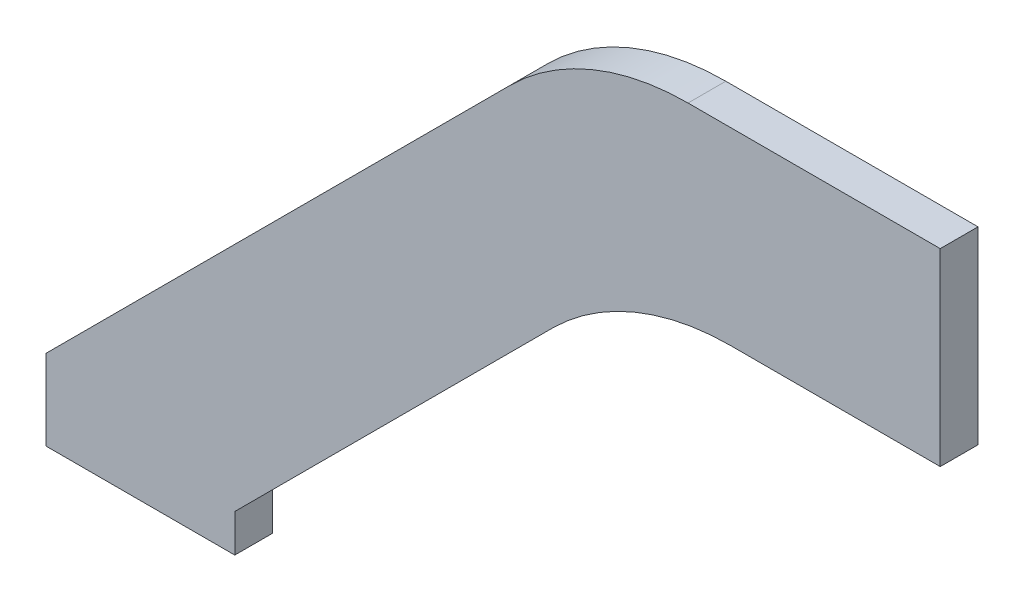
SolidWorks part; units mm, degrees
material "PBT General Purpose"
ref_plane "Front Plane" through (0, 0, 0) normal (0, 0, 1) x (1, 0, 0)
ref_plane "Top Plane" through (0, 0, 0) normal (0, 1, 0) x (1, 0, 0)
ref_plane "Right Plane" through (0, 0, 0) normal (1, 0, 0) x (0, 0, -1)
sketch "Sketch1" plane through (0, 0, 0) normal (0, 0, 1) x (1, 0, 0)
  line L7 (0, 0) -> (1.5, 0)
  line L8 (1.5, 0) -> (1.5, 0.3)
  line L9 (1.5, 0.3) -> (4.6113, 3.4113)
  line L10 (4.6113, 3.4113) -> (7.105, 3.4113)
  line L11 (7.105, 3.4113) -> (7.105, 4.9113)
  line L12 (7.105, 4.9113) -> (4.2728, 4.9113)
  line L13 (4.2728, 4.9113) -> (0, 0.6385)
  line L14 (0, 0.6385) -> (0, 0)
  dimension "D1" = 1.5
  dimension "D2" = 1.5
  dimension "D3" = 0.3
  dimension "D7" = 1.3
  dimension "D6" = 135
  dimension "D5" = 4.4
  dimension "D4" = 5.605
extrude "Boss-Extrude1" add sketch "Sketch1" along normal mid plane 0.3 contours L10 L11 L12 L13 L14 L7 L8 L9
fillet "Fillet1" radius 2 2 edges at (4.6113, 3.4113, 0) (4.2728, 4.9113, 0)
equation "\"t\"= 0.3'thickness of the sheets"
equation "\"FlexJoint\"= 0.15'Width of flextures"
equation "\"FoldJoint\"= 0.4'Width of folding joints"
equation "\"AssembleAngle\"= 90'Angle of assembly parts"
equation "\"D1@Boss-Extrude1\"=\"t\""
equation "\"D4@Sketch1\"=7.18-\"FlexJoint\"/2-1.5"
